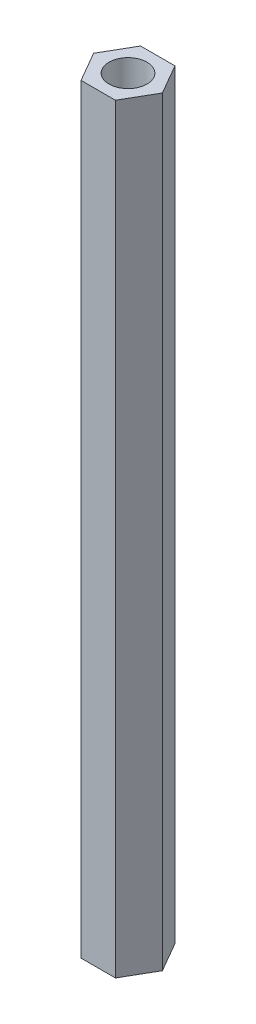
SolidWorks part; units mm, degrees
material "Brass"
ref_plane "Front Plane" through (0, 0, 0) normal (0, 0, 1) x (1, 0, 0)
ref_plane "Top Plane" through (0, 0, 0) normal (0, 1, 0) x (1, 0, 0)
ref_plane "Right Plane" through (0, 0, 0) normal (1, 0, 0) x (0, 0, -1)
sketch "Sketch1" plane through (0, 0, 0) normal (0, 1, 0) x (1, 0, 0)
  line L1 (2.7135, 0) -> (1.3568, 2.35)
  line L2 (1.3568, 2.35) -> (-1.3568, 2.35)
  line L3 (-1.3568, 2.35) -> (-2.7135, 0)
  line L4 (-2.7135, 0) -> (-1.3568, -2.35)
  line L5 (-1.3568, -2.35) -> (1.3568, -2.35)
  line L6 (1.3568, -2.35) -> (2.7135, 0)
  circle A0 centre (0, 0) radius 2.35 construction
  circle A1 centre (0, 0) radius 1.5
extrude "Boss-Extrude1" add sketch "Sketch1" along normal blind 60
